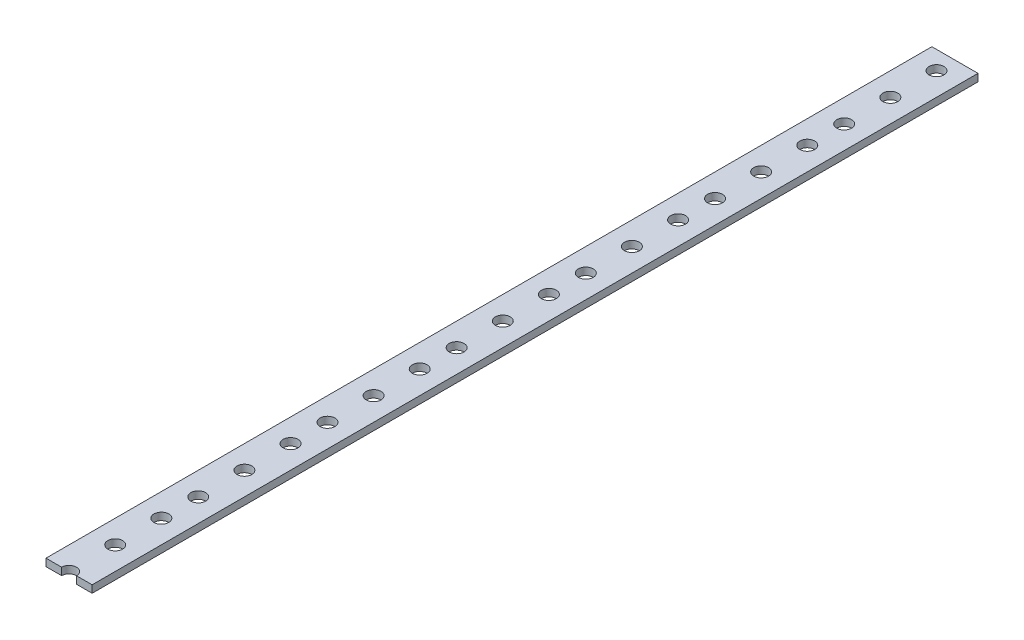
SolidWorks part; units mm, degrees
ref_plane "Front Plane" through (0, 0, 0) normal (0, 0, 1) x (1, 0, 0)
ref_plane "Top Plane" through (0, 0, 0) normal (0, 1, 0) x (1, 0, 0)
ref_plane "Right Plane" through (0, 0, 0) normal (1, 0, 0) x (0, 0, -1)
sketch "Sketch1" plane through (0, 0, 0) normal (0, 1, 0) x (1, 0, 0)
  line L1 (-7.9375, -152.4) -> (7.9375, -152.4)
  line L2 (-7.9375, -152.4) -> (-7.9375, 152.4)
  line L3 (-7.9375, 152.4) -> (7.9375, 152.4)
  line L4 (7.9375, -152.4) -> (7.9375, 152.4)
  line L5 (-7.9375, -152.4) -> (7.9375, 152.4) construction
  line L6 (-7.9375, 152.4) -> (7.9375, -152.4) construction
  point P0 (0, 0)
  dimension "D1" = 15.875
  dimension "D2" = 304.8
extrude "Boss-Extrude1" add sketch "Sketch1" along normal blind 2.54
sketch "Sketch2" plane through (0, 2.54, 0) normal (0, 1, 0) x (1, 0, 0)
  line L0 (7.9375, 152.4) -> (-7.9375, 152.4) construction
  circle A0 centre (0, 146.05) radius 2.5527
  point P2 (0, 145.8272)
  dimension "D1" = 5.1054
  dimension "D2" = 6.35
extrude "Cut-Extrude1" cut sketch "Sketch2" against normal blind 2.54
pattern_linear "LPattern1" count 3 spacing 15.875 along (0, 0, 1) of "Cut-Extrude1"
pattern_linear "LPattern2" count 7 spacing 44.45 along (0, 0, 1) of "LPattern1", "Cut-Extrude1"
